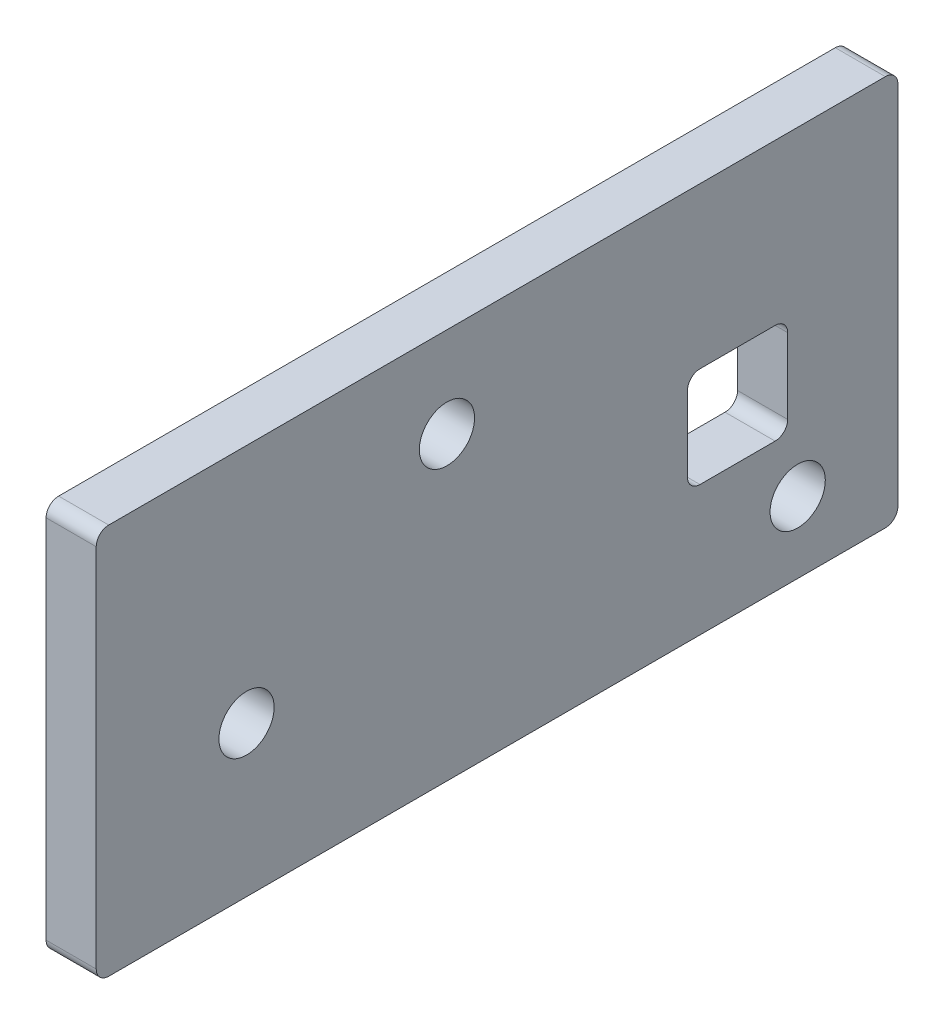
SolidWorks part; units mm, degrees
ref_plane "Front Plane" through (0, 0, 0) normal (1, 0, 0) x (0, 1, 0)
ref_plane "Top Plane" through (0, 0, 0) normal (0, 0, 1) x (0, 1, 0)
ref_plane "Right Plane" through (0, 0, 0) normal (0, 1, 0) x (-1, 0, 0)
sketch "Sketch1" plane through (0, 0, 0) normal (1, 0, 0) x (0, 1, 0)
  line L0 (-31.75, -15.875) -> (31.75, -15.875)
  line L1 (31.75, -34.925) -> (-31.75, -34.925)
  line L2 (31.75, -34.925) -> (31.75, 34.925)
  line L3 (31.75, 34.925) -> (-31.75, 34.925)
  line L4 (-31.75, -34.925) -> (-31.75, 34.925)
  line L5 (31.75, -34.925) -> (-31.75, 34.925) construction
  line L6 (31.75, 34.925) -> (-31.75, -34.925) construction
  line L7 (-22.225, 34.925) -> (22.225, 34.925) construction
  line L8 (-22.225, 34.925) -> (-22.225, 9.525) construction
  line L9 (-22.225, 9.525) -> (22.225, 9.525) construction
  line L10 (22.225, 34.925) -> (22.225, 9.525) construction
  line L12 (-6.985, 34.925) -> (6.985, 34.925)
  line L13 (-6.985, 34.925) -> (-6.985, -15.875)
  line L14 (-6.985, -15.875) -> (6.985, -15.875)
  line L15 (6.985, 34.925) -> (6.985, -15.875)
  line L20 (-23.495, -2.54) -> (-17.145, -2.54)
  line L21 (-23.495, -2.54) -> (-23.495, -8.89)
  line L22 (-23.495, -8.89) -> (-17.145, -8.89)
  line L23 (-17.145, -2.54) -> (-17.145, -8.89)
  circle A0 centre (-27.225, -9.525) radius 5 construction
  circle A1 centre (-27.225, -9.525) radius 1.75
  circle A2 centre (-22.225, 25.4) radius 1.75
  circle A3 centre (-12.7, 12.7) radius 1.75
  point P0 (0, 0)
  point P10 (0, 9.525)
  point P23 (0, -15.875)
  point P32 (-23.495, -5.715)
  point P33 (-20.32, -8.89)
  dimension "D3" = 10
  dimension "D4" = 25.4
  dimension "D6" = 19.05
  dimension "D9" = 3.5
  dimension "D12" = 12.7
  dimension "D1" = 63.5
  dimension "D2" = 44.45
  dimension "D5" = 69.85
  dimension "D7" = 22.225
  dimension "D8" = 25.4
  dimension "D10" = 50.8
  dimension "D11" = 13.97
  dimension "D13" = 12.7
  dimension "D16" = 6.35
  dimension "D17" = 6.35
  dimension "D18" = 18.415
  dimension "D19" = 11.43
extrude "Boss-Extrude1" add sketch "Sketch1" along normal blind 3.175 contours L13 L3 L4 L0 A2 A1
fillet "Fillet1" radius 0.7937 8 edges at (1.5875, -6.985, 34.925) (1.5875, -6.985, -15.875) (1.5875, -31.75, -15.875) (1.5875, -17.145, -8.89) (1.5875, -17.145, -2.54) (1.5875, -23.495, -8.89) (1.5875, -23.495, -2.54) (1.5875, -31.75, 34.925)
